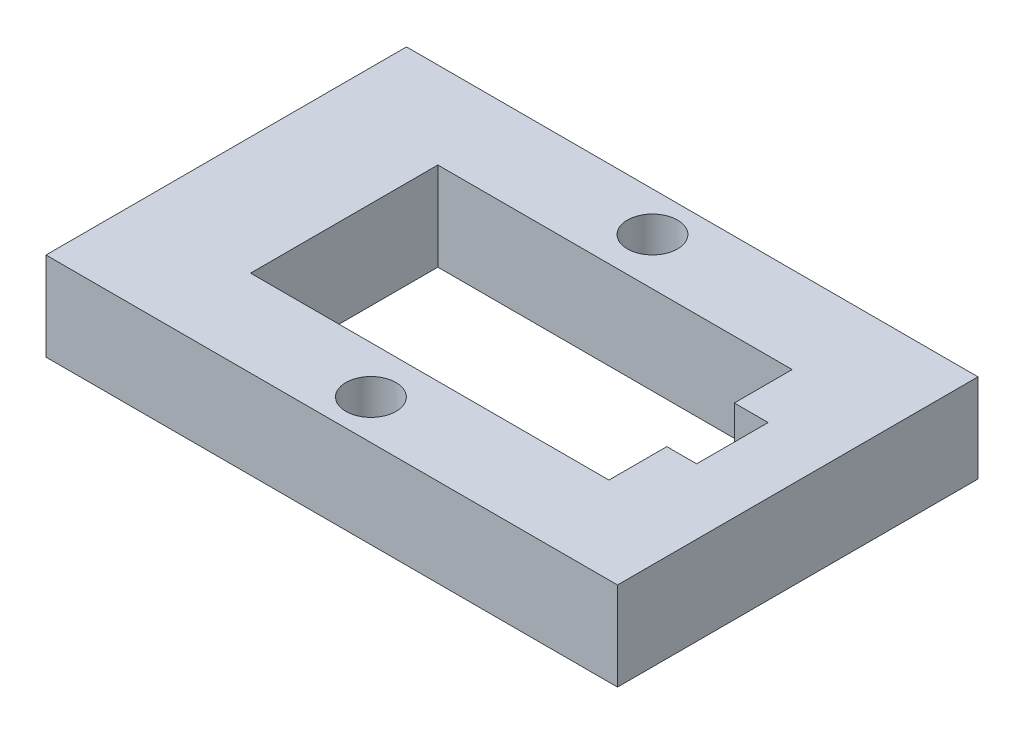
SolidWorks part; units mm, degrees
ref_plane "Front Plane" through (0, 0, 0) normal (0, 0, 1) x (1, 0, 0)
ref_plane "Top Plane" through (0, 0, 0) normal (0, 1, 0) x (1, 0, 0)
ref_plane "Right Plane" through (0, 0, 0) normal (1, 0, 0) x (0, 0, -1)
sketch "Sketch2" plane through (0, 0, 0) normal (0, 1, 0) x (1, 0, 0)
  line L0 (-12.629, 7.7591) -> (11.3956, 7.7591)
  line L1 (-20.629, 13.6321) -> (18.1229, 13.6321)
  line L2 (-20.629, 13.6321) -> (-20.629, -10.8109)
  line L3 (-20.629, -10.8109) -> (18.1229, -10.8109)
  line L4 (18.1229, 13.6321) -> (18.1229, -10.8109)
  line L5 (11.3956, 7.7591) -> (11.3956, 3.8339)
  line L6 (11.3956, 3.8339) -> (13.6929, 3.8339)
  line L7 (13.6929, 3.8339) -> (13.6929, -1.0158)
  line L8 (13.6929, -1.0158) -> (11.671, -1.0158)
  line L9 (11.671, -1.0158) -> (11.671, -4.9409)
  line L10 (11.671, -4.9409) -> (-12.629, -4.9409)
  line L11 (-12.629, -4.9409) -> (-12.629, 7.7591)
  circle A0 centre (-1.2727, 10.9544) radius 1.7
  circle A1 centre (-1.2771, -8.1309) radius 1.7
  dimension "D8" = 3.4
  dimension "D13" = 19.3956
  dimension "D14" = 19.4
  dimension "D2" = 5.87
  dimension "D3" = 12.7
  dimension "D4" = 24.3
  dimension "D5" = 2.0219
  dimension "D6" = 4.8498
  dimension "D7" = 2.6777
  dimension "D9" = 5.873
  dimension "D10" = 2.68
  dimension "D11" = 8
  dimension "D12" = 4.43
extrude "Boss-Extrude1" add sketch "Sketch2" along normal mid plane 6
